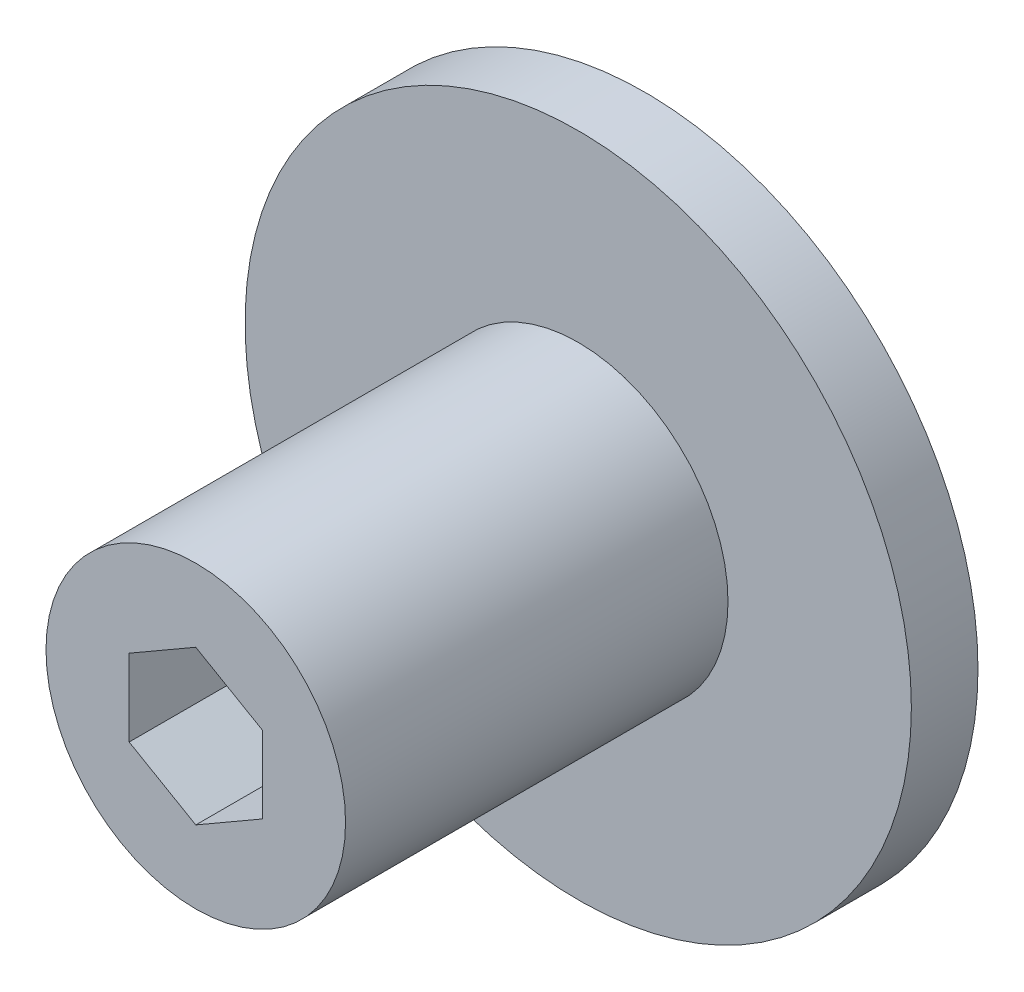
SolidWorks part; units mm, degrees
ref_plane "Front Plane" through (0, 0, 0) normal (0, 0, 1) x (1, 0, 0)
ref_plane "Top Plane" through (0, 0, 0) normal (0, 1, 0) x (1, 0, 0)
ref_plane "Right Plane" through (0, 0, 0) normal (1, 0, 0) x (0, 0, -1)
sketch "Sketch1" plane through (0, 0, 0) normal (0, 0, 1) x (1, 0, 0)
  circle A0 centre (0, 0) radius 31.75
extrude "Boss-Extrude1" add sketch "Sketch1" along normal mid plane 6.35
sketch "Sketch2" plane through (0, 0, 3.175) normal (0, 0, 1) x (1, 0, 0)
  circle A0 centre (0, 0) radius 14.2748
  dimension "D1" = 28.5496
extrude "Boss-Extrude2" add sketch "Sketch2" along normal blind 36.449
sketch "Sketch3" plane through (0, 0, -3.175) normal (0, 0, -1) x (-1, 0, 0)
  line L0 (0, 0) -> (-12.5856, 0) construction
  line L1 (-10.0667, 1.9844) -> (-10.0667, -1.9844)
  line L2 (-10.0667, 1.9844) -> (-7.6855, 1.9844)
  line L3 (-10.0667, -1.9844) -> (-7.6855, -1.9844)
  line L4 (-3.3148, 9.7102) -> (-2.1242, 7.648)
  line L5 (-3.3148, 9.7102) -> (-6.7519, 7.7258)
  line L6 (-6.7519, 7.7258) -> (-5.5612, 5.6636)
  line L7 (6.7519, 7.7258) -> (5.5612, 5.6636)
  line L8 (6.7519, 7.7258) -> (3.3148, 9.7102)
  line L9 (3.3148, 9.7102) -> (2.1242, 7.648)
  line L10 (10.0667, -1.9844) -> (7.6855, -1.9844)
  line L11 (10.0667, -1.9844) -> (10.0667, 1.9844)
  line L12 (10.0667, 1.9844) -> (7.6855, 1.9844)
  line L13 (3.3148, -9.7102) -> (2.1242, -7.648)
  line L14 (3.3148, -9.7102) -> (6.7519, -7.7258)
  line L15 (6.7519, -7.7258) -> (5.5612, -5.6636)
  line L16 (-6.7519, -7.7258) -> (-5.5612, -5.6636)
  line L17 (-6.7519, -7.7258) -> (-3.3148, -9.7102)
  line L18 (-3.3148, -9.7102) -> (-2.1242, -7.648)
  arc A1 (-7.6855, -1.9844) -> (-5.5612, -5.6636) centre (0, 0) ccw
  arc A2 (-5.5612, 5.6636) -> (-7.6855, 1.9844) centre (0, 0) ccw
  arc A3 (2.1242, 7.648) -> (-2.1242, 7.648) centre (0, 0) ccw
  arc A4 (7.6855, 1.9844) -> (5.5612, 5.6636) centre (0, 0) ccw
  arc A5 (5.5612, -5.6636) -> (7.6855, -1.9844) centre (0, 0) ccw
  arc A6 (-2.1242, -7.648) -> (2.1242, -7.648) centre (0, 0) ccw
  point P7 (-10.0667, 0)
  point P30 (8.782, -2.3409)
  dimension "D1" = 15.875
  dimension "D2" = 3.9688
  dimension "D3" = 2.3813
extrude "Cut-Extrude1" cut sketch "Sketch3" against normal blind 25.4
sketch "Sketch4" plane through (0, 0, 39.624) normal (0, 0, 1) x (1, 0, 0)
  line L1 (0, 7.3323) -> (-6.35, 3.6662)
  line L2 (-6.35, 3.6662) -> (-6.35, -3.6662)
  line L3 (-6.35, -3.6662) -> (0, -7.3323)
  line L4 (0, -7.3323) -> (6.35, -3.6662)
  line L5 (6.35, -3.6662) -> (6.35, 3.6662)
  line L6 (6.35, 3.6662) -> (0, 7.3323)
  circle A0 centre (0, 0) radius 6.35 construction
  dimension "D1" = 12.7
extrude "Cut-Extrude2" cut sketch "Sketch4" against normal blind 12.7
